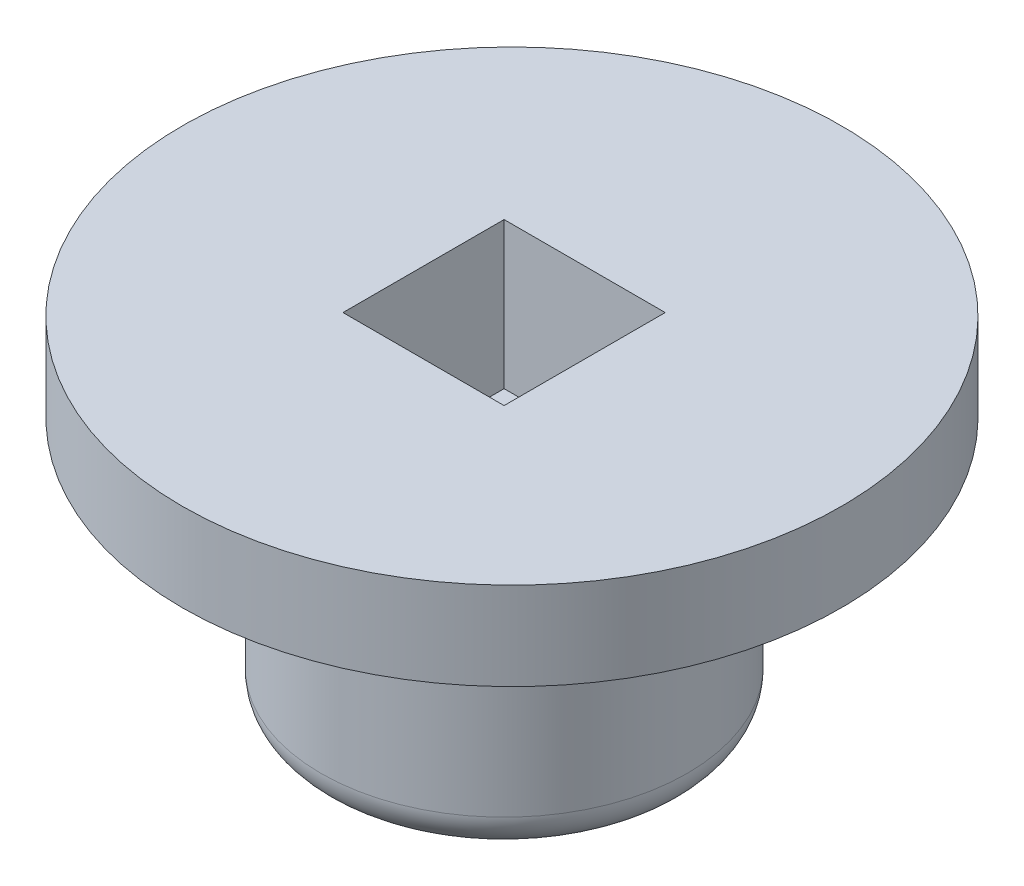
SolidWorks part; units mm, degrees
ref_plane "前视基准面" through (0, 0, 0) normal (0, 0, 1) x (1, 0, 0)
ref_plane "上视基准面" through (0, 0, 0) normal (0, 1, 0) x (1, 0, 0)
ref_plane "右视基准面" through (0, 0, 0) normal (1, 0, 0) x (0, 0, -1)
sketch "草图1" plane through (0, 0, 0) normal (0, 1, 0) x (1, 0, 0)
  circle A0 centre (0, 0) radius 2.5
  dimension "D1" = 5
extrude "凸台-拉伸1" add sketch "草图1" along normal blind 3.5 contours A0
sketch "草图2" plane through (0, 3.5, 0) normal (0, 1, 0) x (1, 0, 0)
  circle A0 centre (0.0949, 0.012) radius 4.5
  dimension "D1" = 9
extrude "凸台-拉伸2" add sketch "草图2" along normal blind 1.2
sketch "草图4" plane through (0, 4.7, 0) normal (0, 1, 0) x (1, 0, 0)
  line L1 (1.1, -1.1) -> (-1.1, -1.1)
  line L2 (1.1, -1.1) -> (1.1, 1.1)
  line L3 (1.1, 1.1) -> (-1.1, 1.1)
  line L4 (-1.1, -1.1) -> (-1.1, 1.1)
  line L5 (1.1, -1.1) -> (-1.1, 1.1) construction
  line L6 (1.1, 1.1) -> (-1.1, -1.1) construction
  circle A0 centre (0, 0) radius 2.5 construction
  point P0 (0, 0)
  point P5 (0, 0)
  point P8 (0, 0)
  dimension "D1" = 2.2
  dimension "D2" = 2.2
extrude "切除-拉伸1" cut sketch "草图4" against normal blind 2
fillet "圆角1" radius 0.5 1 edges at (0, 0, 2.5)
